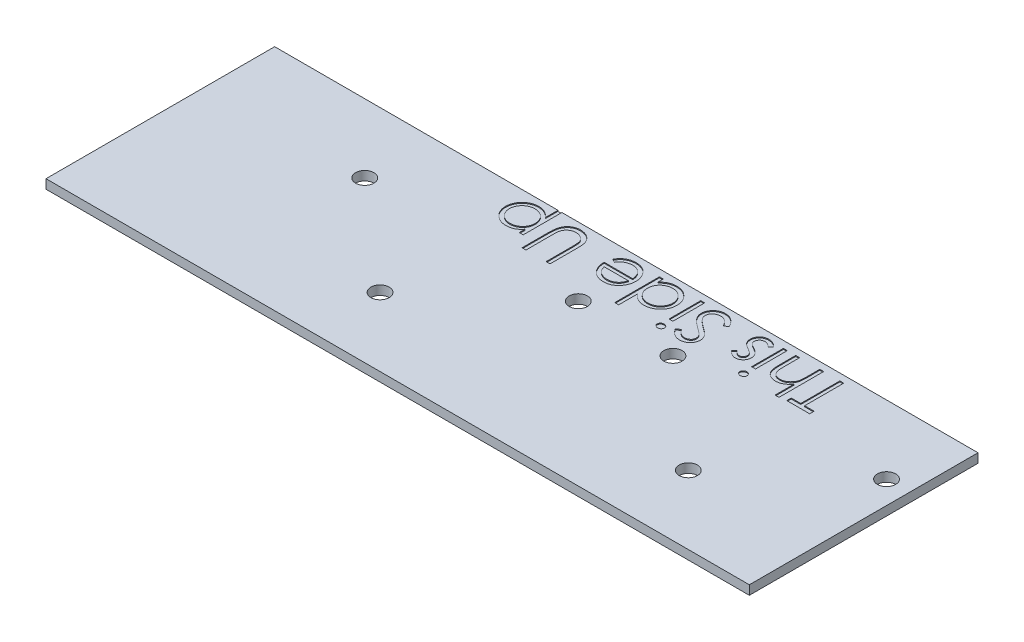
SolidWorks part; units mm, degrees
ref_plane "Front Plane" through (0, 0, 0) normal (0, 0, 1) x (1, 0, 0)
ref_plane "Top Plane" through (0, 0, 0) normal (0, 1, 0) x (1, 0, 0)
ref_plane "Right Plane" through (0, 0, 0) normal (1, 0, 0) x (0, 0, -1)
sketch "Sketch1" plane through (0, 0, 0) normal (0, 1, 0) x (1, 0, 0)
  line L0 (39.05, 25) -> (95.75, 25)
  line L1 (-28.35, 25) -> (28.35, 25)
  line L2 (-28.35, 25) -> (-28.35, -25)
  line L3 (-28.35, -25) -> (28.35, -25)
  line L4 (28.35, 25) -> (28.35, -25)
  line L5 (-28.35, 25) -> (28.35, -25) construction
  line L6 (-28.35, -25) -> (28.35, 25) construction
  line L7 (28.35, 25) -> (37.05, 25)
  line L8 (28.35, 25) -> (28.35, -25)
  line L9 (28.35, -25) -> (37.05, -25)
  line L10 (37.05, 25) -> (37.05, -25)
  line L11 (37.05, 25) -> (39.05, 25)
  line L12 (37.05, 25) -> (37.05, -25)
  line L13 (37.05, -25) -> (39.05, -25)
  line L14 (39.05, 25) -> (39.05, -25)
  line L15 (39.05, 25) -> (39.05, -25)
  line L16 (39.05, -25) -> (95.75, -25)
  line L17 (95.75, 25) -> (95.75, -25)
  line L19 (-28.35, -25) -> (-58.05, -25)
  line L20 (-28.35, -25) -> (-28.35, 25)
  line L21 (-28.35, 25) -> (-58.05, 25)
  line L22 (-58.05, -25) -> (-58.05, 25)
  circle A0 centre (-23.35, 10) radius 2
  circle A1 centre (0, -10) radius 2
  circle A2 centre (23.35, 10) radius 2
  circle A3 centre (44.05, 10) radius 2
  circle A4 centre (67.4, -10) radius 2
  circle A5 centre (90.75, 10) radius 2
  point P0 (0, 0)
  dimension "D2" = 4
  dimension "D3" = 4
  dimension "D4" = 4
  dimension "D5" = 15
  dimension "D6" = 15
  dimension "D14" = 4
  dimension "D15" = 4
  dimension "D16" = 4
  dimension "D17" = 5
  dimension "D18" = 5
  dimension "D19" = 28.35
  dimension "D20" = 35
  dimension "D23" = 15
  dimension "D24" = 15
  dimension "D25" = 29.7
  dimension "D1" = 50
  dimension "D7" = 35
  dimension "D8" = 56.7
  dimension "D9" = 5
  dimension "D10" = 5
  dimension "D11" = 28.35
  dimension "D12" = 50
  dimension "D13" = 56.7
  dimension "D21" = 2
  dimension "D22" = 8.7
extrude "Boss-Extrude1" add sketch "Sketch1" along normal blind 2 contours L4 L1 L2 L3 A2 A1 A0 | L10 L7 L4 L9 | L17 L0 L14 L16 A5 A4 A3 | L14 L11 L10 L13 | L22 L19 L2 L21
sketch "Sketch2" plane through (0, 2, 0) normal (0, 1, 0) x (1, 0, 0)
  line L0 (-3.3, 23.5) -> (70.7, 23.5) construction
  line L1 (-58.05, 25) -> (95.75, 25) construction
  line L2 (95.75, 25) -> (95.75, -25) construction
  line L3 (-28.35, 25) -> (-28.35, -25) construction
  text T0 "This Side Up" font "Century Gothic" height in points 36
  dimension "D1" = 1.5
  dimension "D2" = 74
  dimension "D3" = 25.05
  dimension "D4" = 25.05
extrude "Cut-Extrude1" cut sketch "Sketch2" against normal blind 0.2
